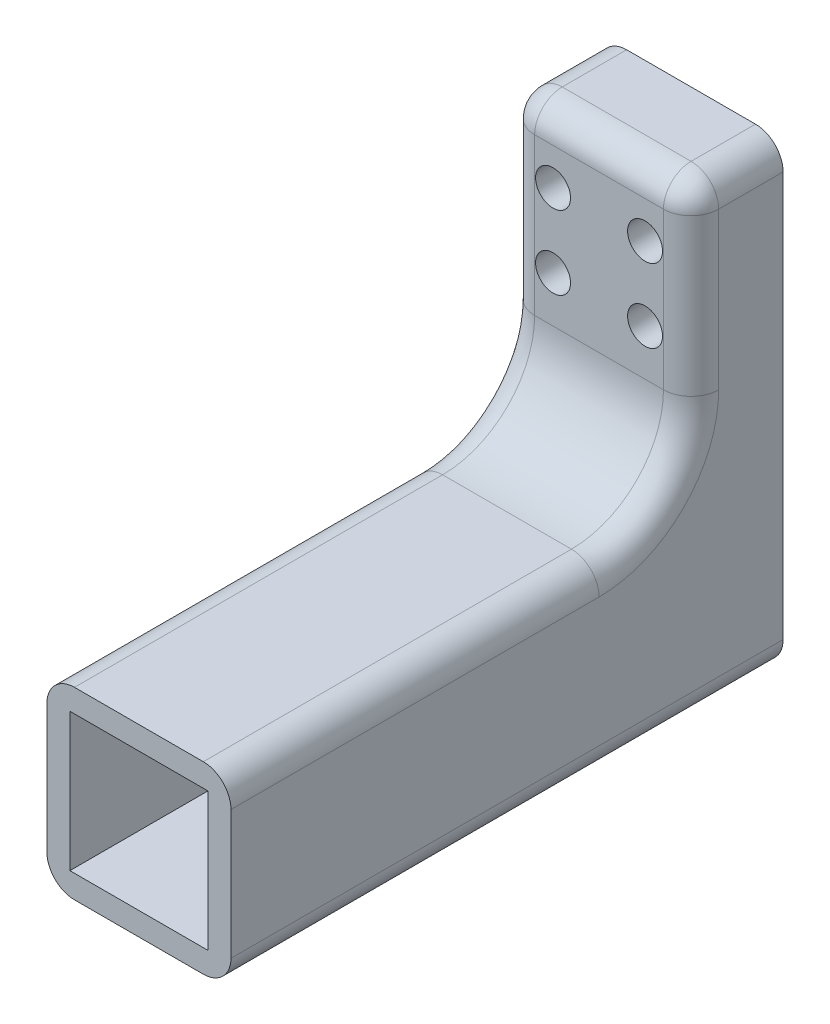
SolidWorks part; units mm, degrees
ref_plane "正面" through (0, 0, 0) normal (0, 0, 1) x (1, 0, 0)
ref_plane "平面" through (0, 0, 0) normal (0, 1, 0) x (1, 0, 0)
ref_plane "右側面" through (0, 0, 0) normal (1, 0, 0) x (0, 0, -1)
sketch "ｽｹｯﾁ4" plane through (0, 0, 0) normal (0, 0, 1) x (1, 0, 0)
  line L1 (-7.5, 7.5) -> (7.5, 7.5)
  line L2 (-7.5, 7.5) -> (-7.5, -7.5)
  line L3 (-7.5, -7.5) -> (7.5, -7.5)
  line L4 (7.5, 7.5) -> (7.5, -7.5)
  line L5 (-7.5, 7.5) -> (7.5, -7.5) construction
  line L6 (-7.5, -7.5) -> (7.5, 7.5) construction
  line L7 (-10, 10) -> (10, 10)
  line L8 (-10, 10) -> (-10, -10)
  line L9 (-10, -10) -> (10, -10)
  line L10 (10, 10) -> (10, -10)
  line L11 (-10, 10) -> (10, -10) construction
  line L12 (-10, -10) -> (10, 10) construction
  point P0 (0, 0)
  point P6 (0, 0)
  dimension "D1" = 15
  dimension "D2" = 20
  dimension "D3" = 15
  dimension "D4" = 20
extrude "ﾎﾞｽ - 押し出し3" add sketch "ｽｹｯﾁ4" along normal blind 60
sketch "ｽｹｯﾁ5" plane through (0, 0, 0) normal (0, 0, 1) x (1, 0, 0)
  line L0 (10, 10) -> (10, 40)
  line L1 (10, 40) -> (-10, 40)
  line L2 (-10, 40) -> (-10, 10)
  line L3 (-10, 10) -> (10, 10)
  dimension "D1" = 40
extrude "ﾎﾞｽ - 押し出し4" add sketch "ｽｹｯﾁ5" along normal blind 10
fillet "ﾌｨﾚｯﾄ1" radius 10 1 edges at (0, 10, 10)
fillet "ﾌｨﾚｯﾄ2" radius 3 9 edges at (-10, 30, 10) (-10, 12.9289, 12.9289) (10, 30, 10) (10, 12.9289, 12.9289) (0, 40, 10) (10, 40, 5) (-10, 40, 5) (-10, 10, 40) (10, 10, 40)
fillet "ﾌｨﾚｯﾄ3" radius 3 2 edges at (10, -10, 30) (-10, -10, 30)
sketch "ｽｹｯﾁ6" plane through (0, 0, 0) normal (0, 0, 1) x (1, 0, 0)
  circle A0 centre (5, 25) radius 1.9
  circle A1 centre (5, 33) radius 1.9
  circle A2 centre (-5, 33) radius 1.9
  circle A3 centre (-5, 25) radius 1.9
  dimension "D7" = 3.8
  dimension "D8" = 3.8
  dimension "D9" = 3.8
  dimension "D10" = 3.8
  dimension "D1" = 25
  dimension "D2" = 25
  dimension "D3" = 8
  dimension "D4" = 8
  dimension "D5" = 5
  dimension "D6" = 5
extrude "ｶｯﾄ - 押し出し1" cut sketch "ｽｹｯﾁ6" along normal blind 10
